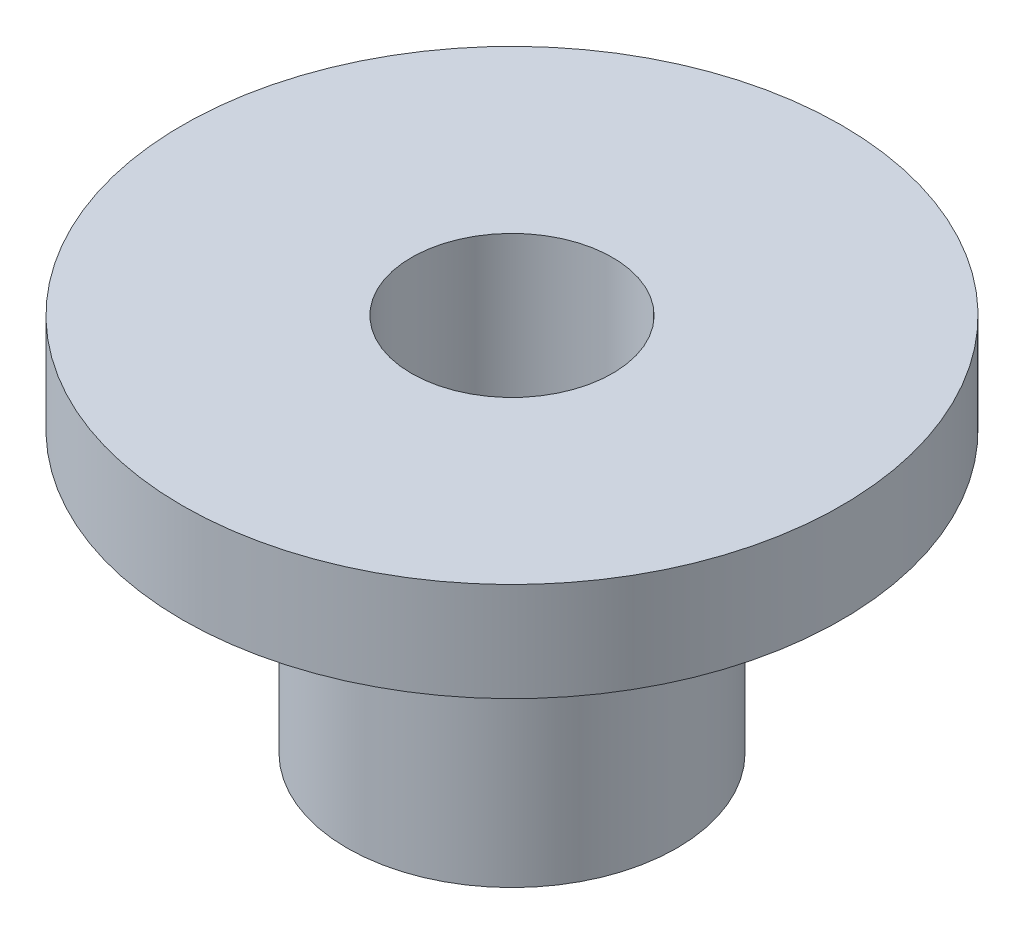
SolidWorks part; units mm, degrees
ref_plane "前视基准面" through (0, 0, 0) normal (0, 0, 1) x (1, 0, 0)
ref_plane "上视基准面" through (0, 0, 0) normal (0, 1, 0) x (1, 0, 0)
ref_plane "右视基准面" through (0, 0, 0) normal (1, 0, 0) x (0, 0, -1)
other "Configuration Table"
sketch "草图1" plane through (0, 0, 0) normal (0, 1, 0) x (1, 0, 0)
  circle A0 centre (0, 0) radius 5
  circle A1 centre (0, 0) radius 3.05
  dimension "D1" = 10
  dimension "D2" = 6.1
extrude "凸台-拉伸1" add sketch "草图1" along normal blind 8.5
sketch "草图2" plane through (0, 8.5, 0) normal (0, 1, 0) x (1, 0, 0)
  circle A0 centre (0, 0) radius 10
  circle A1 centre (0, 0) radius 3.05 construction
  circle A2 centre (0, 0) radius 3.05
  dimension "D1" = 20
extrude "凸台-拉伸2" add sketch "草图2" along normal blind 3
